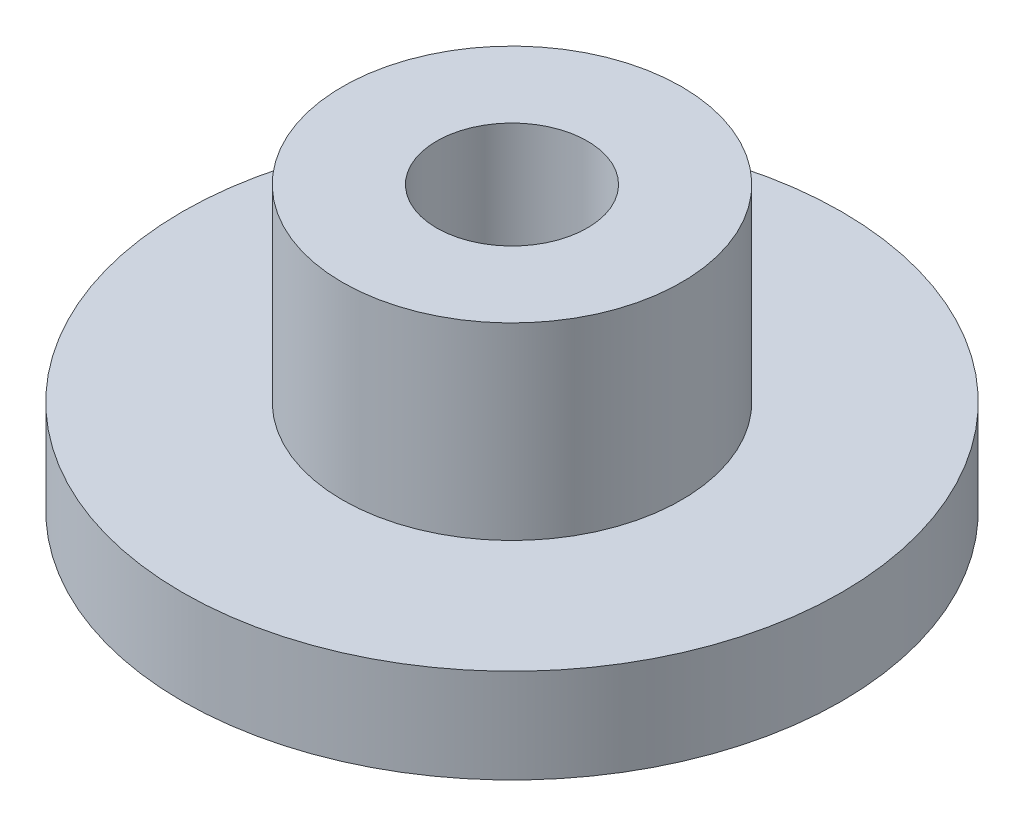
SolidWorks part; units mm, degrees
ref_plane "Front Plane" through (0, 0, 0) normal (0, 0, 1) x (1, 0, 0)
ref_plane "Top Plane" through (0, 0, 0) normal (0, 1, 0) x (1, 0, 0)
ref_plane "Right Plane" through (0, 0, 0) normal (1, 0, 0) x (0, 0, -1)
sketch "Sketch1" plane through (0, 0, 0) normal (0, 1, 0) x (1, 0, 0)
  circle A0 centre (0, 0) radius 17.5
  circle A2 centre (0, 0) radius 2.5
  dimension "D1" = 35
  dimension "D2" = 5
extrude "Boss-Extrude1" add sketch "Sketch1" along normal blind 5
sketch "Sketch2" plane through (0, 5, 0) normal (0, 1, 0) x (1, 0, 0)
  circle A0 centre (0, 0) radius 9
  circle A1 centre (0, 0) radius 4
  dimension "D1" = 8
  dimension "D2" = 18
extrude "Boss-Extrude2" add sketch "Sketch2" along normal blind 10
